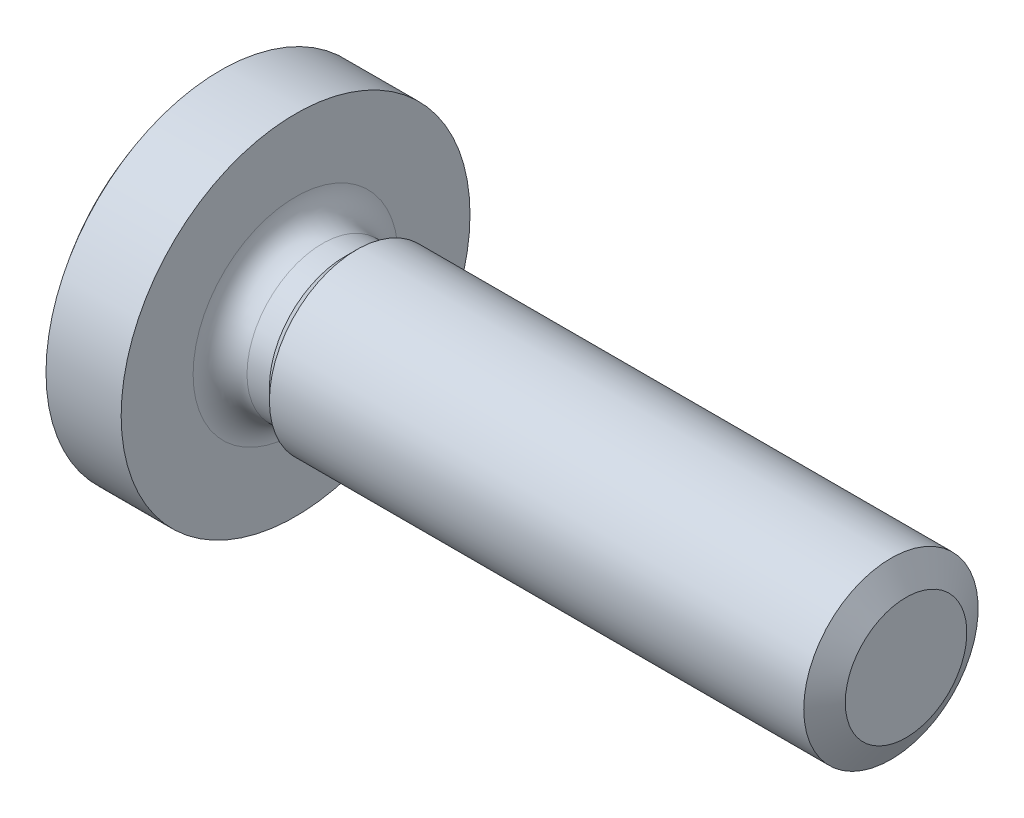
SolidWorks part; units mm, degrees
revolve "基体-旋转" add sketch "草图2" angle 360 about L0
sketch "草图2" plane through (0, 0, 0) normal (0, 0, 1) x (1, 0, 0)
  line L0 (-1.3318, 0) -> (6.5885, 0) construction
  line L1 (0, 0) -> (17.1, 0)
  line L2 (17.1, 0) -> (17.1, 2)
  line L3 (17.1, 2) -> (4.5, 2)
  line L4 (4.5, 2) -> (4.232, 1.732)
  line L5 (4.232, 1.732) -> (3.718, 1.732)
  line L6 (3.1, 2.35) -> (3.1, 4)
  line L7 (3.1, 4) -> (1.3765, 4)
  arc A0 (3.1, 2.35) -> (3.718, 1.732) centre (3.718, 2.35) ccw
  arc A1 (0, 0) -> (1.3765, 4) centre (6.5, 0) cw
  dimension "D3" = 6.5
  dimension "dk" = 8
  dimension "d" = 4
  dimension "l" = 14
  dimension "a" = 1.4
  dimension "D1" = 45
  dimension "D2" = 3.464
  dimension "da" = 4.7
  dimension "k" = 3.1
cosmetic thread "装饰螺纹线1" parameters "D1"=12.6, "D2"=3.464
material "钢"
ref_plane "前视" through (0, 0, 0) normal (0, 0, 1) x (1, 0, 0)
ref_plane "上视" through (0, 0, 0) normal (0, 1, 0) x (1, 0, 0)
ref_plane "右视" through (0, 0, 0) normal (1, 0, 0) x (0, 0, -1)
sketch "尺寸草图" plane through (0, 0, 0) normal (0, 0, 1) x (1, 0, 0)
  line L0 (0, 0) -> (14, 0)
  line L1 (0, 0) -> (0, 8)
  line L2 (14, 0) -> (14, 4.7)
  point P5 (0, 4)
  point P6 (13.3, 0)
  point P7 (1.4, 0)
  point P8 (3.1, 0)
  point P9 (7.5, 0)
  point P10 (4.4, 0)
  point P11 (11.6, 0)
  dimension "dk" = 8
  dimension "d" = 4
  dimension "l" = 14
  dimension "a" = 1.4
  dimension "da" = 4.7
  dimension "k" = 3.1
  dimension "P" = 0.7
  dimension "rf" = 6.5
  dimension "m" = 4.4
  dimension "h" = 2.4
sketch "草图3" plane through (0, 0, 0) normal (0, 0, 1) x (1, 0, 0)
  line L0 (16.7538, 2) -> (17.4538, 2)
  line L1 (17.4538, 2) -> (17.1, 1.3938)
  line L2 (17.1, 1.3938) -> (16.7538, 2)
  line L3 (17.1, 2) -> (4.5, 2) construction
  line L4 (17.1, -2) -> (17.1, 2) construction
  line L5 (-0.2428, 0) -> (7.1644, 0) construction
  line L6 (-1.3318, 0) -> (6.5885, 0) construction
  dimension "P" = 0.7
  dimension "D1" = 0.6062
  dimension "D2" = 60
revolve "切除-旋转1" cut sketch "草图3" angle 360 about L5
sketch "草图5" plane through (0, 0, 0) normal (1, 0, 0) x (0, 0, -1)
  line L1 (0.35, 2.2) -> (-0.35, 2.2)
  line L2 (0.35, 2.2) -> (0.35, -2.2)
  line L3 (0.35, -2.2) -> (-0.35, -2.2)
  line L4 (-0.35, 2.2) -> (-0.35, -2.2)
  point P4 (0.35, 0)
  point P5 (0, 2.2)
  dimension "m" = 4.4
  dimension "D1" = 0.7
ref_plane "基准面1" through (2.4, 0, 0) normal (1, 0, 0) x (0, 0, -1)
pattern_linear "阵列(线性)1" [suppressed] count 19 spacing 0.7 along (1, 0, 0)
sketch "草图6" plane through (2.4, 0, 0) normal (1, 0, 0) x (0, 0, -1)
  point P0 (0, 0)
loft "切除-放样1" cut profiles "草图6", "草图5"
ref_plane "基准面2" through (0, 0, 0) normal (0, -0.7071, 0.7071) x (1, 0, 0)
mirror "镜向1" about plane through (0, 0, 0) normal (0, -0.7071, 0.7071) of "切除-放样1"
equation "\"l@草图2\" = \"l@尺寸草图\""
equation "\"dk@草图2\" = \"dk@尺寸草图\""
equation "\"k@草图2\" = \"k@尺寸草图\""
equation "\"D2@草图2\" = \"d@尺寸草图\"*0.866"
equation "\"a@草图2\" = \"a@尺寸草图\""
equation "\"D3@草图2\" = \"rf@尺寸草图\""
equation "\"d@草图2\" = \"d@尺寸草图\""
equation "\"da@草图2\" = \"da@尺寸草图\""
equation "\"D2@装饰螺纹线1\" = \"d@尺寸草图\"*0.866"
equation "\"D1@装饰螺纹线1\" = \"l@尺寸草图\"-\"a@尺寸草图\""
equation "\"P@草图3\" = \"P@尺寸草图\""
equation "\"D1@草图3\" = \"P@尺寸草图\"*0.866"
equation "\"h@基准面1\" = \"h@尺寸草图\""
equation "\"D1@草图5\" = \"P@尺寸草图\""
equation "\"m@草图5\" = \"m@尺寸草图\""
equation "\"D3@阵列(线性)1\" = \"P@尺寸草图\""
equation "\"D1@阵列(线性)1\" = (\"l@尺寸草图\"-\"a@尺寸草图\")/\"P@尺寸草图\"+1"
